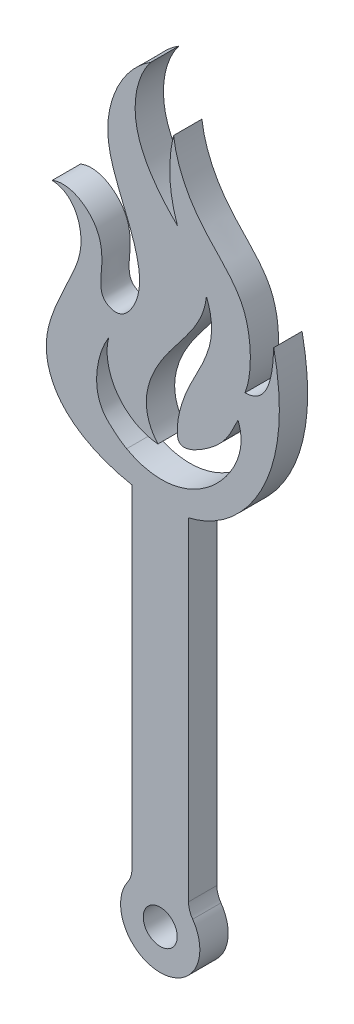
SolidWorks part; units mm, degrees
ref_plane "前视基准面" through (0, 0, 0) normal (0, 0, 1) x (1, 0, 0)
ref_plane "上视基准面" through (0, 0, 0) normal (0, 1, 0) x (1, 0, 0)
ref_plane "右视基准面" through (0, 0, 0) normal (1, 0, 0) x (0, 0, -1)
sketch "草图1" plane through (0, 0, 0) normal (0, 0, 1) x (1, 0, 0)
  line L0 (0, 0) -> (0, 33.1623) construction
  line L1 (-2.5, 3.1623) -> (-2.5, 33.1623)
  line L2 (2.5, 3.1623) -> (2.5, 33.1623)
  line L3 (-2.5, 33.1623) -> (2.5, 33.1623)
  circle A0 centre (0, 0) radius 1.5
  arc A1 (-2.8636, 2.0124) -> (2.8636, 2.0124) centre (0, 0) ccw
  arc A2 (-2.5, 3.1623) -> (-2.8636, 2.0124) centre (-4.5, 3.1623) cw
  arc A3 (2.5, 3.1623) -> (2.8636, 2.0124) centre (4.5, 3.1623) ccw
  point P11 (-2.5, 2.4495)
  point P14 (2.5, 2.4495)
  dimension "D1" = 7
  dimension "D2" = 3
  dimension "D3" = 2
  dimension "D4" = 5
  dimension "D5" = 30
extrude "凸台-拉伸1" add sketch "草图1" along normal blind 2.5
sketch "草图3" plane through (0, 0, 0) normal (0, 0, 1) x (1, 0, 0)
  line L0 (82.5866, -234.3938) -> (489.2533, -234.3938) construction
  spline S0 degree 3 poles (1.6995, 32.3699) (-1.3851, 31.947) (-8.1308, 33.1856) (-10.8595, 40.2676) (-8.3371, 44.4676) (-6.4702, 49.1927) (-7.6528, 52.2078) (-9.5388, 52.2986) knots 0 0 0 0 0.389446 0.476704 0.741561 0.833904 1 1 1 1
  spline S1 degree 3 poles (-9.5388, 52.2986) (-8.0405, 52.9262) (-5.2697, 51.2361) (-5.048, 48.0048) (-5.4627, 45.556) (-3.3505, 44.6292) (-1.6818, 47.0507) (-1.8435, 50.0938) (-3.268, 53.7325) (-5.6939, 59.1885) (-3.3221, 64.1139) (-0.8484, 65.6664) knots 0 0 0 0 0.135074 0.221027 0.289623 0.317982 0.397027 0.482985 0.593401 0.740558 1 1 1 1
  spline S2 degree 3 poles (-0.8484, 65.6664) (-2.0232, 64.1412) (-2.967, 59.57) (-0.0771, 55.9205) (1.518, 54.3682) knots 0 0 0 0 0.453669 1 1 1 1
  spline S3 degree 2 poles (1.518, 54.3682) (0.3587, 57.6638) (1.1782, 61.0895) knots 0 0 0 1 1 1
  spline S4 degree 3 poles (1.1782, 61.0895) (1.4547, 58.9636) (3.2212, 55.3695) (7.3256, 52.1053) (8.0998, 47.9498) (7.9099, 45.704) (7.4854, 44.5694) knots 0 0 0 0 0.342133 0.634925 0.806626 1 1 1 1
  spline S5 degree 3 poles (7.4854, 44.5694) (9.8147, 44.5707) (9.9544, 47.7175) (10.0215, 49.2926) knots 0 0 0 0 1 1 1 1
  spline S6 degree 3 poles (10.0215, 49.2926) (10.5629, 46.6911) (10.8474, 41.9965) (8.0191, 35.3829) (4.2466, 32.719) (1.6995, 32.3699) knots 0 0 0 0 0.383345 0.656086 1 1 1 1
  spline S7 degree 3 poles (-2.9622, 35.0702) (-1.8361, 34.433) (1.6477, 33.6809) (6.288, 36.8512) (7.4815, 40.6623) (6.8714, 42.1716) knots 0 0 0 0 0.254824 0.682331 1 1 1 1
  spline S9 degree 3 poles (6.8714, 42.1716) (6.1835, 40.7579) (5.5424, 39.3058) (1.5045, 36.9924) (1.4865, 39.1234) (1.7069, 40.3764) (2.3171, 42.2155) (3.5084, 44.4006) (4.7785, 47.1549) (4.4668, 49.3077) (4.0778, 50.239) knots 0 0 0 0 0.205208 0.355343 0.404867 0.471007 0.557598 0.689136 0.848468 1 1 1 1
  spline S10 degree 3 poles (4.0778, 50.239) (3.9171, 48.4878) (2.1392, 46.0584) (-0.9766, 42.1953) (-1.7999, 38.6647) (-0.2061, 36.8079) knots 0 0 0 0 0.339222 0.587957 1 1 1 1
  spline S11 degree 3 poles (-0.2061, 36.8079) (-1.5753, 36.9208) (-4.2212, 38.3937) (-4.9138, 41.429) (-4.5448, 42.7863) knots 0 0 0 0 0.493076 1 1 1 1
  spline S12 degree 3 poles (-4.5448, 42.7863) (-5.5271, 41.2259) (-6.2848, 37.9469) (-4.1059, 35.855) (-3.49, 35.3689) (-2.9622, 35.0702) knots 0 0 0 0 0.715193 0.811866 1 1 1 1
extrude "凸台-拉伸2" add sketch "草图3" along normal up to surface (2.5 mm away) up to face at (0, 11.8509, 2.5)
